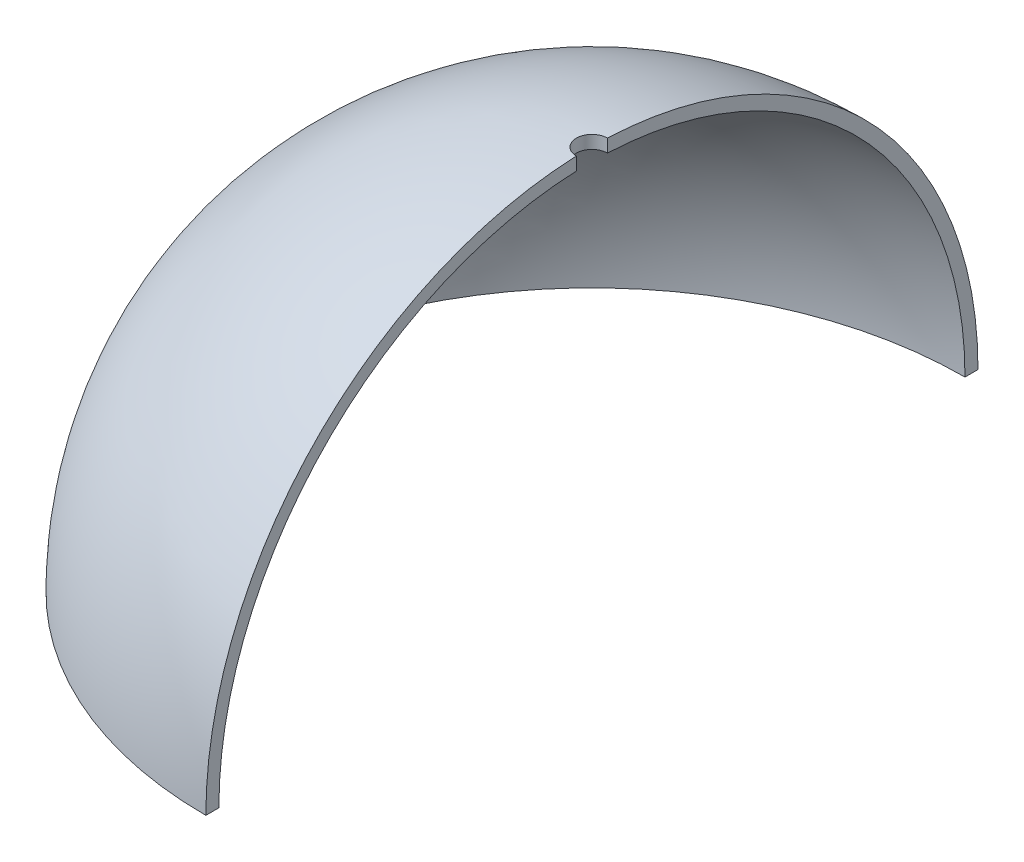
SolidWorks part; units mm, degrees
ref_plane "Front" through (0, 0, 0) normal (0, 0, 1) x (1, 0, 0)
ref_plane "Top" through (0, 0, 0) normal (0, 1, 0) x (1, 0, 0)
ref_plane "Right" through (0, 0, 0) normal (1, 0, 0) x (0, 0, -1)
sketch "Sketch2" plane through (0, 0, 0) normal (0, 1, 0) x (1, 0, 0)
  line L0 (0, -9945) -> (0, -9610)
  line L1 (0, 9610) -> (0, 9945)
  line L2 (0, -3077.1526) -> (0, 2858.4717) construction
  line L3 (0, -55) -> (0, 55) construction
  arc A0 (0, 9610) -> (0, -9610) centre (0, 0) ccw
  arc A1 (0, 9945) -> (0, -9945) centre (0, 0) ccw
  dimension "D1" = 9945
  dimension "D2" = 9610
revolve "Revolve1" add sketch "Sketch2" angle 90 about L2
sketch "Sketch3" plane through (0, 0, 0) normal (0, 1, 0) x (1, 0, 0)
  circle A0 centre (0, 0) radius 400
extrude "Cut-Extrude1" cut sketch "Sketch3" along normal up to surface (9936.9525 mm away)
